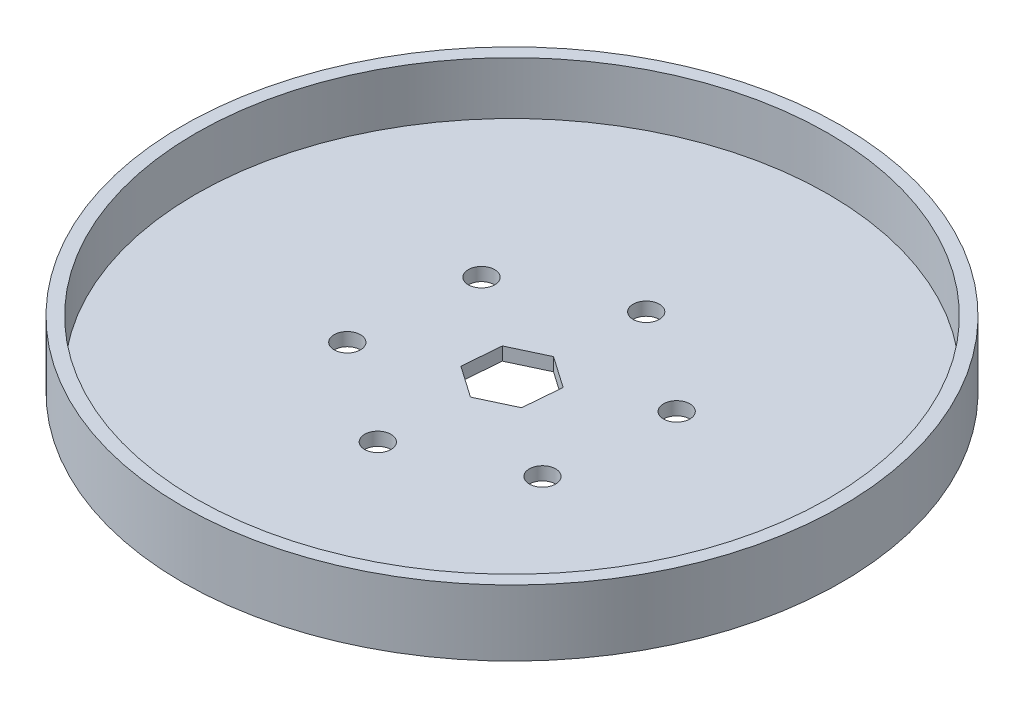
SolidWorks part; units mm, degrees
ref_plane "Front Plane" through (0, 0, 0) normal (0, 0, 1) x (1, 0, 0)
ref_plane "Top Plane" through (0, 0, 0) normal (0, 1, 0) x (1, 0, 0)
ref_plane "Right Plane" through (0, 0, 0) normal (1, 0, 0) x (0, 0, -1)
sketch "Sketch1" plane through (0, 0, 0) normal (0, 1, 0) x (1, 0, 0)
  circle A0 centre (0, 0) radius 63.5
  dimension "D1" = 127
extrude "Boss-Extrude1" add sketch "Sketch1" against normal blind 12.7
sketch "Sketch7" plane through (0, 0, 0) normal (0, 1, 0) x (1, 0, 0)
  circle A6 centre (19.563, -13.6877) radius 2.54
  circle A8 centre (21.6354, 10.0982) radius 2.54
  circle A9 centre (2.0724, 23.7859) radius 2.54
  circle A10 centre (-19.563, 13.6877) radius 2.54
  circle A11 centre (-21.6354, -10.0982) radius 2.54
  circle A12 centre (-2.0724, -23.7859) radius 2.54
  point P15 (0, 0)
  dimension "D1" = 23.876
  dimension "D2" = 6
extrude "Cut-Extrude2" cut sketch "Sketch7" against normal through all
sketch "Sketch8" plane through (0, 0, 0) normal (0, 1, 0) x (1, 0, 0)
  line L1 (-6.7021, -3.1504) -> (-0.6227, -7.3794)
  line L2 (-0.6227, -7.3794) -> (6.0794, -4.229)
  line L3 (6.0794, -4.229) -> (6.7021, 3.1504)
  line L4 (6.7021, 3.1504) -> (0.6227, 7.3794)
  line L5 (0.6227, 7.3794) -> (-6.0794, 4.229)
  line L6 (-6.0794, 4.229) -> (-6.7021, -3.1504)
  circle A0 centre (0, 0) radius 6.4135 construction
  point P1 (0, 7.4057)
  point P9 (0, 0)
  point P11 (0.3839, 7.3957)
  point P12 (1.3305, 7.2852)
  point P13 (0.825, 7.3596)
  point P14 (-6.8783, -2.7446)
  point P15 (-6.4135, -3.103)
  point P16 (-6.6943, -3.1671)
  point P17 (-6.7021, -3.1504)
  dimension "D1" = 12.827
extrude "Cut-Extrude3" cut sketch "Sketch8" against normal through all
shell "Shell1" thickness 2.54
